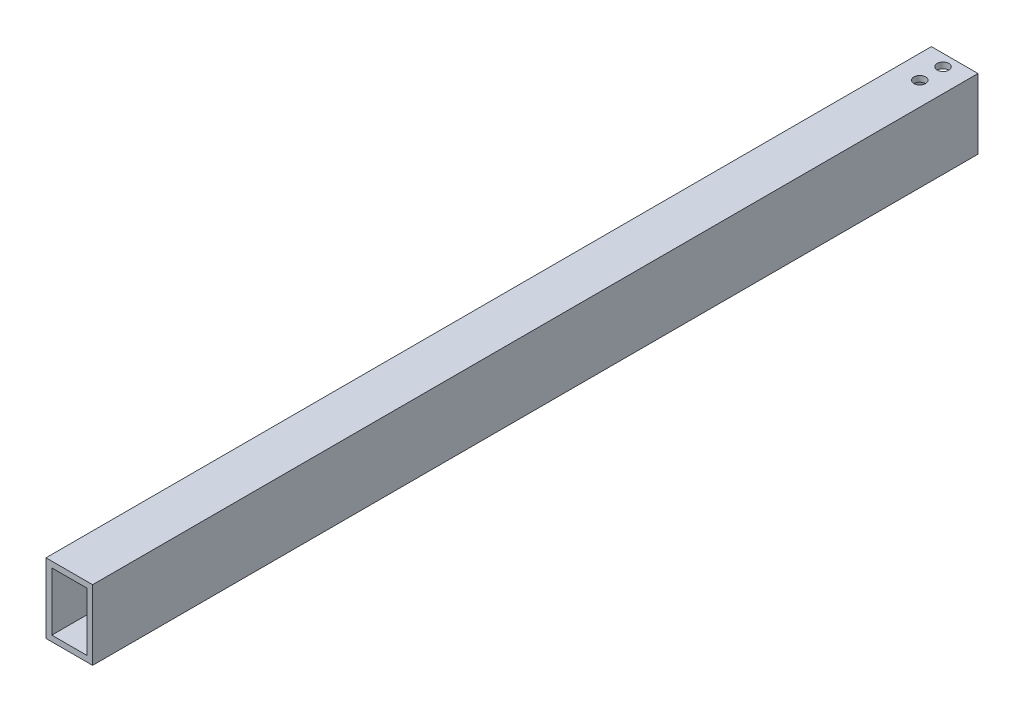
SolidWorks part; units mm, degrees
ref_plane "Front Plane" through (0, 0, 0) normal (0, 0, 1) x (1, 0, 0)
ref_plane "Top Plane" through (0, 0, 0) normal (0, 1, 0) x (1, 0, 0)
ref_plane "Right Plane" through (0, 0, 0) normal (1, 0, 0) x (0, 0, -1)
sketch "Sketch1" plane through (0, 0, 0) normal (0, 0, 1) x (1, 0, 0)
  line L1 (-12.7, 19.05) -> (12.7, 19.05)
  line L2 (-12.7, 19.05) -> (-12.7, -19.05)
  line L3 (-12.7, -19.05) -> (12.7, -19.05)
  line L4 (12.7, 19.05) -> (12.7, -19.05)
  line L5 (-12.7, 19.05) -> (12.7, -19.05) construction
  line L6 (-12.7, -19.05) -> (12.7, 19.05) construction
  line L7 (-9.525, -15.875) -> (9.525, -15.875)
  line L8 (-9.525, -15.875) -> (-9.525, 15.875)
  line L9 (-9.525, 15.875) -> (9.525, 15.875)
  line L10 (9.525, -15.875) -> (9.525, 15.875)
  line L11 (-9.525, -15.875) -> (9.525, 15.875) construction
  line L12 (-9.525, 15.875) -> (9.525, -15.875) construction
  point P0 (0, 0)
  point P6 (0, 0)
  dimension "D1" = 25.4
  dimension "D2" = 38.1
  dimension "D3" = 3.175
  dimension "D4" = 3.175
extrude "Boss-Extrude1" add sketch "Sketch1" along normal blind 482.6
sketch "Sketch2" plane through (0, 19.05, 0) normal (0, 1, 0) x (1, 0, 0)
  line L2 (-12.7, 0) -> (12.7, 0) construction
  circle A0 centre (0, -19.05) radius 3.175
  circle A1 centre (0, -6.35) radius 3.175
  dimension "D1" = 6.35
  dimension "D2" = 6.35
  dimension "D3" = 6.35
  dimension "D4" = 12.7
extrude "Cut-Extrude1" cut sketch "Sketch2" against normal through all
